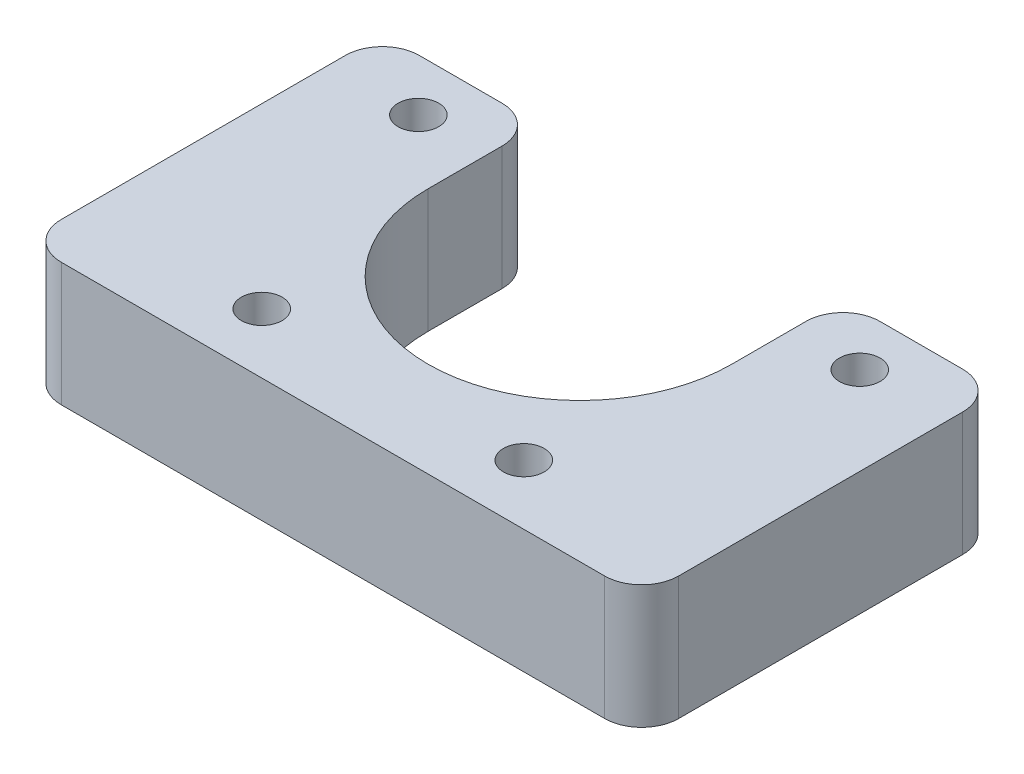
SolidWorks part; units mm, degrees
ref_plane "前视基准面" through (0, 0, 0) normal (0, 0, 1) x (1, 0, 0)
ref_plane "上视基准面" through (0, 0, 0) normal (0, 1, 0) x (1, 0, 0)
ref_plane "右视基准面" through (0, 0, 0) normal (1, 0, 0) x (0, 0, -1)
other "Configuration Table"
sketch "草图1" plane through (0, 0, 0) normal (0, 1, 0) x (1, 0, 0)
  line L0 (0, 50.7801) -> (0, -54.8652) construction
  line L1 (-25, -30) -> (25, -30) construction
  line L2 (-25, -30) -> (-25, 30) construction
  line L3 (-25, 30) -> (25, 30) construction
  line L4 (25, -30) -> (25, 30) construction
  line L5 (-25, -30) -> (25, 30) construction
  line L6 (-25, 30) -> (25, -30) construction
  line L7 (-12.3, 30) -> (-25, 30) construction
  line L8 (-25, 30) -> (-25, 10)
  line L9 (-25, 10) -> (25, 10)
  line L10 (25, 10) -> (25, 30)
  line L11 (25, 30) -> (12.3, 30) construction
  line L12 (-12.3, 30) -> (-12.3, 39)
  line L13 (-12.3, 39) -> (-25, 39)
  line L14 (-25, 39) -> (-25, 30)
  line L15 (0, 30) -> (-10.6112, 14.8457) construction
  line L16 (0, 30) -> (-17.8696, 34.7882) construction
  line L17 (12.3, 30) -> (12.3, 39)
  line L18 (25, 39) -> (25, 30)
  line L19 (12.3, 39) -> (25, 39)
  arc A0 (-12.3, 30) -> (12.3, 30) centre (0, 30) ccw
  circle A1 centre (0, 30) radius 18.5 construction
  circle A2 centre (-10.6112, 14.8457) radius 1.65
  circle A3 centre (-17.8696, 34.7882) radius 1.65
  circle A4 centre (10.6112, 14.8457) radius 1.65
  circle A5 centre (17.8696, 34.7882) radius 1.65
  point P0 (0, 0)
  dimension "D1" = 12.3
  dimension "D4" = 37
  dimension "D8" = 3.3
  dimension "D2" = 50
  dimension "D3" = 20
  dimension "D5" = 60
  dimension "D6" = 35
  dimension "D7" = 70
  dimension "D9" = 9
extrude "凸台-拉伸1" add sketch "草图1" along normal blind 10
fillet "圆角1" radius 3 6 edges at (-25, 5, -10) (-25, 5, -39) (-12.3, 5, -39) (12.3, 5, -39) (25, 5, -39) (25, 5, -10)
